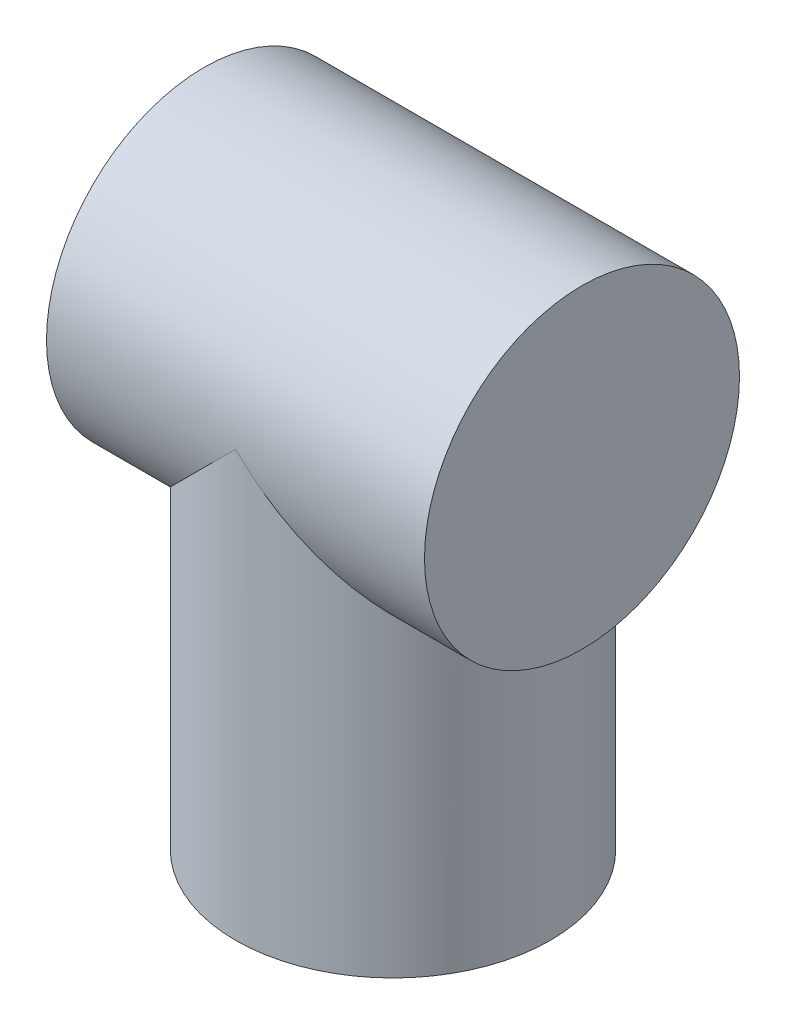
SolidWorks part; units mm, degrees
ref_plane "前视基准面" through (0, 0, 0) normal (0, 0, 1) x (1, 0, 0)
ref_plane "上视基准面" through (0, 0, 0) normal (0, 1, 0) x (1, 0, 0)
ref_plane "右视基准面" through (0, 0, 0) normal (1, 0, 0) x (0, 0, -1)
sketch "草图1" plane through (0, 0, 0) normal (0, 1, 0) x (1, 0, 0)
  circle A0 centre (0, 0) radius 50
  dimension "D1" = 100
extrude "凸台-拉伸1" add sketch "草图1" along normal blind 135
sketch "草图2" plane through (0, 0, 0) normal (1, 0, 0) x (0, 0, -1)
  line L0 (50, 135) -> (-50, 135) construction
  line L4 (50, 0) -> (50, 135) construction
  circle A0 centre (0, 135) radius 50
extrude "凸台-拉伸2" add sketch "草图2" along normal mid plane 120
